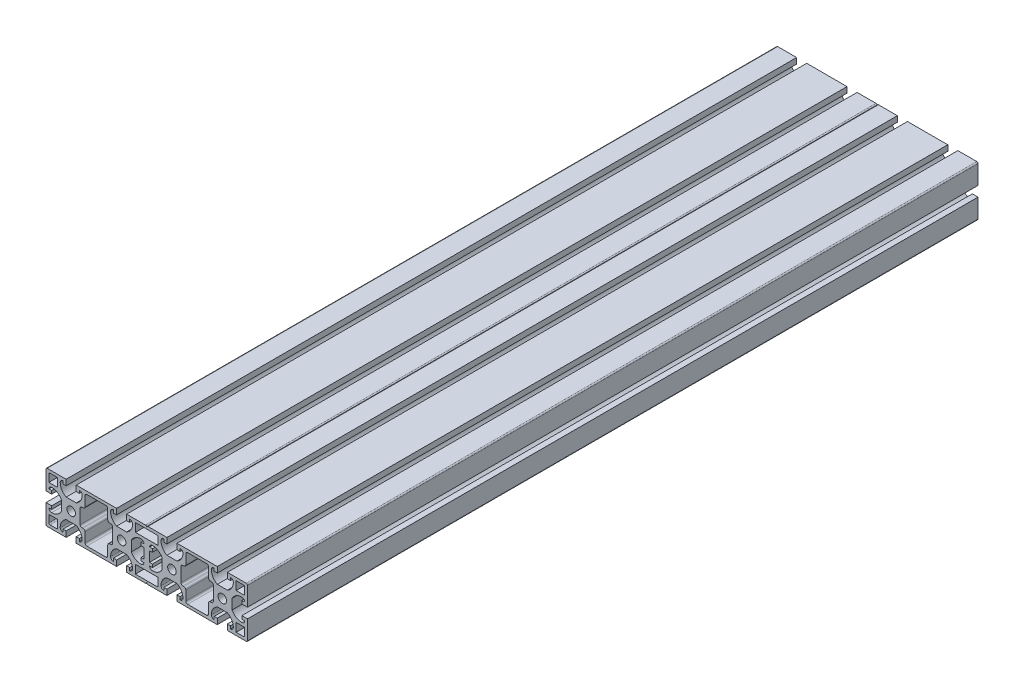
SolidWorks part; units mm, degrees
material "3.0255 (EN-AW 1350A)"
ref_plane "Płaszczyzna przednia" through (0, 0, 0) normal (0, 0, 1) x (1, 0, 0)
ref_plane "Płaszczyzna górna" through (0, 0, 0) normal (0, 1, 0) x (1, 0, 0)
ref_plane "Płaszczyzna prawa" through (0, 0, 0) normal (1, 0, 0) x (0, 0, -1)
sketch "Szkic1" plane through (0, 0, 0) normal (0, 0, 1) x (1, 0, 0)
  line L0 (0, 20) -> (0, -20) construction
  line L1 (-51.8865, 0) -> (40, 0) construction
  line L4 (-40, -19) -> (-40, 19)
  line L7 (-40, -20) -> (0, 0) construction
  line L8 (-40, 20) -> (40, -20) construction
  line L13 (20, 20) -> (20, 0) construction
  line L15 (24, 20) -> (24, 15.5)
  line L16 (24, 15.5) -> (26.4714, 15.5)
  line L21 (16, 15.5) -> (13.5286, 15.5)
  line L23 (16, 20) -> (13.5286, 20)
  line L24 (16, 20) -> (16, 15.5)
  line L25 (16, 7.75) -> (24, 7.75)
  line L26 (13.5286, 15.5) -> (13.5286, 17.75)
  line L27 (26.4714, 15.5) -> (26.4714, 17.75)
  line L28 (-24, 20) -> (-24, 15.5)
  line L29 (-26.4714, 15.5) -> (-26.4714, 17.75)
  line L30 (-24, 15.5) -> (-26.4714, 15.5)
  line L31 (-13.5286, 15.5) -> (-13.5286, 17.75)
  line L32 (-16, 15.5) -> (-13.5286, 15.5)
  line L33 (-16, 20) -> (-16, 15.5)
  line L34 (-16, 7.75) -> (-24, 7.75)
  line L35 (20, -20) -> (20, 0) construction
  line L36 (-40, -20) -> (0, 0) construction
  line L37 (-40, 20) -> (40, -20) construction
  line L38 (30.9714, -17.75) -> (36.75, -17.75)
  line L39 (-16, -7.75) -> (-24, -7.75)
  line L40 (-16, -20) -> (-16, -15.5)
  line L41 (-16, -15.5) -> (-13.5286, -15.5)
  line L42 (-13.5286, -15.5) -> (-13.5286, -17.75)
  line L43 (-24, -15.5) -> (-26.4714, -15.5)
  line L44 (-26.4714, -15.5) -> (-26.4714, -17.75)
  line L45 (-24, -20) -> (-24, -15.5)
  line L46 (26.4714, -15.5) -> (26.4714, -17.75)
  line L47 (13.5286, -15.5) -> (13.5286, -17.75)
  line L48 (16, -7.75) -> (24, -7.75)
  line L49 (16, -20) -> (16, -15.5)
  line L50 (16, -15.5) -> (13.5286, -15.5)
  line L51 (24, -15.5) -> (26.4714, -15.5)
  line L52 (24, -20) -> (24, -15.5)
  line L53 (40, -20) -> (0, 20) construction
  line L54 (35.5, 6.4714) -> (37.75, 6.4714)
  line L55 (35.5, 4) -> (35.5, 6.4714)
  line L56 (40, 4) -> (35.5, 4)
  line L57 (40, -4) -> (35.5, -4)
  line L58 (35.5, -4) -> (35.5, -6.4714)
  line L59 (35.5, -6.4714) -> (37.75, -6.4714)
  line L60 (27.75, 4) -> (27.75, -4)
  line L61 (-35.5, -6.4714) -> (-37.75, -6.4714)
  line L62 (-37.75, -4) -> (-35.5, -4)
  line L63 (-35.5, -4) -> (-35.5, -6.4714)
  line L64 (-35.5, 4) -> (-35.5, 6.4714)
  line L65 (-35.5, 6.4714) -> (-37.75, 6.4714)
  line L66 (-37.75, 4) -> (-35.5, 4)
  line L67 (-27.75, 4) -> (-27.75, -4)
  line L68 (-37.75, 4) -> (-37.75, -4)
  line L69 (40, -4) -> (40, -19)
  line L70 (40, 19) -> (40, 4)
  line L71 (-39, -20) -> (-24, -20)
  line L72 (-16, -20) -> (16, -20)
  line L73 (24, -20) -> (39, -20)
  line L74 (13.5286, 20) -> (-16, 20)
  line L75 (-24, 20) -> (-39, 20)
  line L76 (24, 20) -> (39, 20)
  line L77 (10.5286, 7.0902) -> (11.4095, 7.0902)
  line L78 (-7.5286, -17.75) -> (7.5286, -17.75)
  line L79 (-9.0286, -16.25) -> (-9.0286, -8.5902)
  line L80 (-7.5286, 17.75) -> (7.5286, 17.75)
  line L81 (9.0286, -16.25) -> (9.0286, -8.5902)
  line L82 (-9.0286, -17.75) -> (9.0286, 17.75) construction
  line L83 (-9.0286, 17.75) -> (9.0286, -17.75) construction
  line L84 (-11.4095, -7.0902) -> (-10.5286, -7.0902)
  line L85 (-12.9095, -5.5902) -> (-12.9095, 5.5902)
  line L86 (-11.4095, 7.0902) -> (-10.5286, 7.0902)
  line L87 (12.9095, -5.5902) -> (12.9095, 5.5902)
  line L88 (-12.9095, -7.0902) -> (0, 0) construction
  line L89 (-12.9095, 7.0902) -> (12.9095, -7.0902) construction
  line L90 (-9.0286, 8.5902) -> (-9.0286, 16.25)
  line L91 (-9.0286, 4.5143) -> (-9.0286, 4.9587)
  line L92 (-9.0286, -4.9587) -> (-9.0286, -4.5143)
  line L93 (9.0286, 8.5902) -> (9.0286, 16.25)
  line L94 (10.5286, -7.0902) -> (11.4095, -7.0902)
  line L96 (0, 0) -> (12.9095, 7.0902) construction
  line L98 (37.75, -10.9714) -> (37.75, -16.75)
  line L99 (30.9714, 10.9714) -> (37.75, 10.9714)
  line L100 (30.9714, 10.9714) -> (30.9714, 17.75)
  line L101 (30.9714, 17.75) -> (36.75, 17.75)
  line L102 (37.75, 10.9714) -> (37.75, 16.75)
  line L103 (30.9714, 10.9714) -> (37.75, 17.75) construction
  line L104 (30.9714, 17.75) -> (37.75, 10.9714) construction
  line L105 (30.9714, -10.9714) -> (37.75, -10.9714)
  line L106 (30.9714, -10.9714) -> (30.9714, -17.75)
  line L107 (-30.9714, -10.9714) -> (-30.9714, -17.75)
  line L108 (-30.9714, -10.9714) -> (-37.75, -10.9714)
  line L109 (-37.75, -10.9714) -> (-37.75, -16.75)
  line L110 (-30.9714, -17.75) -> (-36.75, -17.75)
  line L111 (-30.9714, 17.75) -> (-36.75, 17.75)
  line L112 (-37.75, 10.9714) -> (-37.75, 16.75)
  line L113 (-30.9714, 10.9714) -> (-37.75, 10.9714)
  line L114 (-30.9714, 10.9714) -> (-30.9714, 17.75)
  line L115 (-40, 52.1634) -> (-40, -64.8993) construction
  line L116 (-110.9714, 17.75) -> (-117.75, 10.9714) construction
  line L117 (-110.9714, 10.9714) -> (-117.75, 17.75) construction
  line L118 (-80, 0) -> (-92.9095, 7.0902) construction
  line L119 (-67.0905, 7.0902) -> (-92.9095, -7.0902) construction
  line L120 (-67.0905, -7.0902) -> (-80, 0) construction
  line L121 (-70.9714, 17.75) -> (-89.0286, -17.75) construction
  line L122 (-70.9714, -17.75) -> (-89.0286, 17.75) construction
  line L123 (-120, -20) -> (-80, 20) construction
  line L124 (-40, 20) -> (-120, -20) construction
  line L125 (-40, -20) -> (-80, 0) construction
  line L126 (-100, -20) -> (-100, 0) construction
  line L127 (-100, 20) -> (-100, 0) construction
  line L128 (-40, 20) -> (-120, -20) construction
  line L129 (-40, -20) -> (-80, 0) construction
  line L130 (-28.1135, 0) -> (-120, 0) construction
  line L131 (-80, 20) -> (-80, -20) construction
  line L132 (-49.0286, 10.9714) -> (-49.0286, 17.75)
  line L133 (-49.0286, 10.9714) -> (-42.25, 10.9714)
  line L134 (-42.25, 10.9714) -> (-42.25, 16.75)
  line L135 (-49.0286, 17.75) -> (-43.25, 17.75)
  line L136 (-49.0286, -17.75) -> (-43.25, -17.75)
  line L137 (-42.25, -10.9714) -> (-42.25, -16.75)
  line L138 (-49.0286, -10.9714) -> (-42.25, -10.9714)
  line L139 (-49.0286, -10.9714) -> (-49.0286, -17.75)
  line L140 (-110.9714, -10.9714) -> (-110.9714, -17.75)
  line L141 (-110.9714, -10.9714) -> (-117.75, -10.9714)
  line L142 (-117.75, 10.9714) -> (-117.75, 16.75)
  line L143 (-110.9714, 17.75) -> (-116.75, 17.75)
  line L144 (-110.9714, 10.9714) -> (-110.9714, 17.75)
  line L145 (-110.9714, 10.9714) -> (-117.75, 10.9714)
  line L146 (-117.75, -10.9714) -> (-117.75, -16.75)
  line L147 (-90.5286, -7.0902) -> (-91.4095, -7.0902)
  line L148 (-89.0286, 8.5902) -> (-89.0286, 16.25)
  line L149 (-70.9714, -4.9587) -> (-70.9714, -4.5143)
  line L150 (-70.9714, 4.5143) -> (-70.9714, 4.9587)
  line L151 (-70.9714, 8.5902) -> (-70.9714, 16.25)
  line L152 (-92.9095, -5.5902) -> (-92.9095, 5.5902)
  line L153 (-68.5905, 7.0902) -> (-69.4714, 7.0902)
  line L154 (-67.0905, -5.5902) -> (-67.0905, 5.5902)
  line L155 (-68.5905, -7.0902) -> (-69.4714, -7.0902)
  line L156 (-89.0286, -16.25) -> (-89.0286, -8.5902)
  line L157 (-72.4714, 17.75) -> (-87.5286, 17.75)
  line L158 (-70.9714, -16.25) -> (-70.9714, -8.5902)
  line L159 (-72.4714, -17.75) -> (-87.5286, -17.75)
  line L160 (-90.5286, 7.0902) -> (-91.4095, 7.0902)
  line L161 (-104, 20) -> (-119, 20)
  line L162 (-56, 20) -> (-41, 20)
  line L163 (-93.5286, 20) -> (-64, 20)
  line L164 (-104, -20) -> (-119, -20)
  line L165 (-64, -20) -> (-96, -20)
  line L166 (-41, -20) -> (-56, -20)
  line L167 (-120, 19) -> (-120, 4)
  line L168 (-120, -4) -> (-120, -19)
  line L169 (-42.25, 4) -> (-42.25, -4)
  line L170 (-52.25, 4) -> (-52.25, -4)
  line L171 (-42.25, 4) -> (-44.5, 4)
  line L172 (-44.5, 6.4714) -> (-42.25, 6.4714)
  line L173 (-44.5, 4) -> (-44.5, 6.4714)
  line L174 (-44.5, -4) -> (-44.5, -6.4714)
  line L175 (-42.25, -4) -> (-44.5, -4)
  line L176 (-44.5, -6.4714) -> (-42.25, -6.4714)
  line L177 (-107.75, 4) -> (-107.75, -4)
  line L178 (-115.5, -6.4714) -> (-117.75, -6.4714)
  line L179 (-115.5, -4) -> (-115.5, -6.4714)
  line L180 (-120, -4) -> (-115.5, -4)
  line L181 (-120, 4) -> (-115.5, 4)
  line L182 (-115.5, 4) -> (-115.5, 6.4714)
  line L183 (-115.5, 6.4714) -> (-117.75, 6.4714)
  line L184 (-104, -20) -> (-104, -15.5)
  line L185 (-104, -15.5) -> (-106.4714, -15.5)
  line L186 (-96, -15.5) -> (-93.5286, -15.5)
  line L187 (-96, -20) -> (-96, -15.5)
  line L188 (-96, -7.75) -> (-104, -7.75)
  line L189 (-93.5286, -15.5) -> (-93.5286, -17.75)
  line L190 (-106.4714, -15.5) -> (-106.4714, -17.75)
  line L191 (-56, -20) -> (-56, -15.5)
  line L192 (-53.5286, -15.5) -> (-53.5286, -17.75)
  line L193 (-56, -15.5) -> (-53.5286, -15.5)
  line L194 (-66.4714, -15.5) -> (-66.4714, -17.75)
  line L195 (-64, -15.5) -> (-66.4714, -15.5)
  line L196 (-64, -20) -> (-64, -15.5)
  line L197 (-64, -7.75) -> (-56, -7.75)
  line L198 (-110.9714, -17.75) -> (-116.75, -17.75)
  line L199 (-64, 7.75) -> (-56, 7.75)
  line L200 (-64, 20) -> (-64, 15.5)
  line L201 (-64, 15.5) -> (-66.4714, 15.5)
  line L202 (-66.4714, 15.5) -> (-66.4714, 17.75)
  line L203 (-56, 15.5) -> (-53.5286, 15.5)
  line L204 (-53.5286, 15.5) -> (-53.5286, 17.75)
  line L205 (-56, 20) -> (-56, 15.5)
  line L206 (-106.4714, 15.5) -> (-106.4714, 17.75)
  line L207 (-93.5286, 15.5) -> (-93.5286, 17.75)
  line L208 (-96, 7.75) -> (-104, 7.75)
  line L209 (-96, 20) -> (-96, 15.5)
  line L210 (-96, 20) -> (-93.5286, 20)
  line L211 (-96, 15.5) -> (-93.5286, 15.5)
  line L212 (-104, 15.5) -> (-106.4714, 15.5)
  line L213 (-104, 20) -> (-104, 15.5)
  line L214 (-41, 20) -> (-39, 20)
  line L215 (-43.25, 17.75) -> (-36.75, 17.75)
  line L216 (-42.25, 10.9714) -> (-37.75, 10.9714)
  line L217 (-42.25, -10.9714) -> (-37.75, -10.9714)
  line L218 (-43.25, -17.75) -> (-36.75, -17.75)
  line L219 (-41, -20) -> (-39, -20)
  circle A0 centre (-20, 0) radius 3.4
  circle A1 centre (20, 0) radius 3.4
  arc A2 (26.4714, 17.75) -> (28.7214, 15.5) centre (26.4714, 15.5) cw
  arc A3 (28.7214, 15.5) -> (24, 7.75) centre (20, 15.5) cw
  arc A4 (13.5286, 17.75) -> (11.2786, 15.5) centre (13.5286, 15.5) ccw
  arc A5 (11.2786, 15.5) -> (16, 7.75) centre (20, 15.5) ccw
  arc A6 (-26.4714, 17.75) -> (-28.7214, 15.5) centre (-26.4714, 15.5) ccw
  arc A7 (-13.5286, 17.75) -> (-11.2786, 15.5) centre (-13.5286, 15.5) cw
  arc A8 (-11.2786, 15.5) -> (-16, 7.75) centre (-20, 15.5) cw
  arc A9 (-28.7214, 15.5) -> (-24, 7.75) centre (-20, 15.5) ccw
  arc A10 (-28.7214, -15.5) -> (-24, -7.75) centre (-20, -15.5) cw
  arc A11 (-11.2786, -15.5) -> (-16, -7.75) centre (-20, -15.5) ccw
  arc A12 (-13.5286, -17.75) -> (-11.2786, -15.5) centre (-13.5286, -15.5) ccw
  arc A13 (-26.4714, -17.75) -> (-28.7214, -15.5) centre (-26.4714, -15.5) cw
  arc A14 (11.2786, -15.5) -> (16, -7.75) centre (20, -15.5) cw
  arc A15 (13.5286, -17.75) -> (11.2786, -15.5) centre (13.5286, -15.5) cw
  arc A16 (28.7214, -15.5) -> (24, -7.75) centre (20, -15.5) ccw
  arc A17 (26.4714, -17.75) -> (28.7214, -15.5) centre (26.4714, -15.5) ccw
  arc A18 (35.5, 8.7214) -> (27.75, 4) centre (35.5, 0) ccw
  arc A19 (37.75, 6.4714) -> (35.5, 8.7214) centre (35.5, 6.4714) ccw
  arc A20 (37.75, -6.4714) -> (35.5, -8.7214) centre (35.5, -6.4714) cw
  arc A21 (35.5, -8.7214) -> (27.75, -4) centre (35.5, 0) cw
  arc A22 (-35.5, -8.7214) -> (-27.75, -4) centre (-35.5, 0) ccw
  arc A23 (-37.75, -6.4714) -> (-35.5, -8.7214) centre (-35.5, -6.4714) ccw
  arc A24 (-37.75, 6.4714) -> (-35.5, 8.7214) centre (-35.5, 6.4714) cw
  arc A25 (-35.5, 8.7214) -> (-27.75, 4) centre (-35.5, 0) cw
  arc A26 (-10.5286, 7.0902) -> (-9.0286, 8.5902) centre (-10.5286, 8.5902) ccw
  arc A27 (-9.0286, -8.5902) -> (-10.5286, -7.0902) centre (-10.5286, -8.5902) ccw
  arc A28 (11.4095, -7.0902) -> (12.9095, -5.5902) centre (11.4095, -5.5902) ccw
  arc A29 (9.0286, -8.5902) -> (10.5286, -7.0902) centre (10.5286, -8.5902) cw
  arc A30 (7.5286, -17.75) -> (9.0286, -16.25) centre (7.5286, -16.25) ccw
  arc A31 (-7.5286, -17.75) -> (-9.0286, -16.25) centre (-7.5286, -16.25) cw
  arc A32 (-11.4095, -7.0902) -> (-12.9095, -5.5902) centre (-11.4095, -5.5902) cw
  arc A33 (-12.9095, 5.5902) -> (-11.4095, 7.0902) centre (-11.4095, 5.5902) cw
  arc A34 (-9.0286, 16.25) -> (-7.5286, 17.75) centre (-7.5286, 16.25) cw
  arc A35 (7.5286, 17.75) -> (9.0286, 16.25) centre (7.5286, 16.25) cw
  arc A36 (11.4095, 7.0902) -> (12.9095, 5.5902) centre (11.4095, 5.5902) cw
  arc A37 (10.5286, 7.0902) -> (9.0286, 8.5902) centre (10.5286, 8.5902) cw
  arc A38 (-40, 19) -> (-39, 20) centre (-39, 19) cw
  arc A39 (-39, -20) -> (-40, -19) centre (-39, -19) cw
  arc A40 (39, -20) -> (40, -19) centre (39, -19) ccw
  arc A41 (39, 20) -> (40, 19) centre (39, 19) cw
  arc A42 (36.75, 17.75) -> (37.75, 16.75) centre (36.75, 16.75) cw
  arc A43 (36.75, -17.75) -> (37.75, -16.75) centre (36.75, -16.75) ccw
  arc A44 (-36.75, -17.75) -> (-37.75, -16.75) centre (-36.75, -16.75) cw
  arc A45 (-36.75, 17.75) -> (-37.75, 16.75) centre (-36.75, 16.75) ccw
  arc A46 (-43.25, 17.75) -> (-42.25, 16.75) centre (-43.25, 16.75) cw
  arc A47 (-43.25, -17.75) -> (-42.25, -16.75) centre (-43.25, -16.75) ccw
  arc A48 (-116.75, -17.75) -> (-117.75, -16.75) centre (-116.75, -16.75) cw
  arc A49 (-116.75, 17.75) -> (-117.75, 16.75) centre (-116.75, 16.75) ccw
  arc A50 (-119, 20) -> (-120, 19) centre (-119, 19) ccw
  arc A51 (-119, -20) -> (-120, -19) centre (-119, -19) cw
  arc A52 (-41, -20) -> (-40, -19) centre (-41, -19) ccw
  arc A53 (-40, 19) -> (-41, 20) centre (-41, 19) ccw
  arc A54 (-90.5286, 7.0902) -> (-89.0286, 8.5902) centre (-90.5286, 8.5902) ccw
  arc A55 (-91.4095, 7.0902) -> (-92.9095, 5.5902) centre (-91.4095, 5.5902) ccw
  arc A56 (-87.5286, 17.75) -> (-89.0286, 16.25) centre (-87.5286, 16.25) ccw
  arc A57 (-70.9714, 16.25) -> (-72.4714, 17.75) centre (-72.4714, 16.25) ccw
  arc A58 (-67.0905, 5.5902) -> (-68.5905, 7.0902) centre (-68.5905, 5.5902) ccw
  arc A59 (-68.5905, -7.0902) -> (-67.0905, -5.5902) centre (-68.5905, -5.5902) ccw
  arc A60 (-72.4714, -17.75) -> (-70.9714, -16.25) centre (-72.4714, -16.25) ccw
  arc A61 (-87.5286, -17.75) -> (-89.0286, -16.25) centre (-87.5286, -16.25) cw
  arc A62 (-89.0286, -8.5902) -> (-90.5286, -7.0902) centre (-90.5286, -8.5902) ccw
  arc A63 (-91.4095, -7.0902) -> (-92.9095, -5.5902) centre (-91.4095, -5.5902) cw
  arc A64 (-70.9714, -8.5902) -> (-69.4714, -7.0902) centre (-69.4714, -8.5902) cw
  arc A65 (-69.4714, 7.0902) -> (-70.9714, 8.5902) centre (-69.4714, 8.5902) cw
  arc A66 (-44.5, 8.7214) -> (-52.25, 4) centre (-44.5, 0) ccw
  arc A67 (-42.25, 6.4714) -> (-44.5, 8.7214) centre (-44.5, 6.4714) ccw
  arc A68 (-42.25, -6.4714) -> (-44.5, -8.7214) centre (-44.5, -6.4714) cw
  arc A69 (-44.5, -8.7214) -> (-52.25, -4) centre (-44.5, 0) cw
  arc A70 (-115.5, -8.7214) -> (-107.75, -4) centre (-115.5, 0) ccw
  arc A71 (-117.75, -6.4714) -> (-115.5, -8.7214) centre (-115.5, -6.4714) ccw
  arc A72 (-117.75, 6.4714) -> (-115.5, 8.7214) centre (-115.5, 6.4714) cw
  arc A73 (-115.5, 8.7214) -> (-107.75, 4) centre (-115.5, 0) cw
  arc A74 (-106.4714, -17.75) -> (-108.7214, -15.5) centre (-106.4714, -15.5) cw
  arc A75 (-108.7214, -15.5) -> (-104, -7.75) centre (-100, -15.5) cw
  arc A76 (-93.5286, -17.75) -> (-91.2786, -15.5) centre (-93.5286, -15.5) ccw
  arc A77 (-91.2786, -15.5) -> (-96, -7.75) centre (-100, -15.5) ccw
  arc A78 (-53.5286, -17.75) -> (-51.2786, -15.5) centre (-53.5286, -15.5) ccw
  arc A79 (-66.4714, -17.75) -> (-68.7214, -15.5) centre (-66.4714, -15.5) cw
  arc A80 (-68.7214, -15.5) -> (-64, -7.75) centre (-60, -15.5) cw
  arc A81 (-51.2786, -15.5) -> (-56, -7.75) centre (-60, -15.5) ccw
  arc A82 (-51.2786, 15.5) -> (-56, 7.75) centre (-60, 15.5) cw
  arc A83 (-68.7214, 15.5) -> (-64, 7.75) centre (-60, 15.5) ccw
  arc A84 (-66.4714, 17.75) -> (-68.7214, 15.5) centre (-66.4714, 15.5) ccw
  arc A85 (-53.5286, 17.75) -> (-51.2786, 15.5) centre (-53.5286, 15.5) cw
  arc A86 (-91.2786, 15.5) -> (-96, 7.75) centre (-100, 15.5) cw
  arc A87 (-93.5286, 17.75) -> (-91.2786, 15.5) centre (-93.5286, 15.5) cw
  arc A88 (-108.7214, 15.5) -> (-104, 7.75) centre (-100, 15.5) ccw
  arc A89 (-106.4714, 17.75) -> (-108.7214, 15.5) centre (-106.4714, 15.5) ccw
  circle A90 centre (-100, 0) radius 3.4
  circle A91 centre (-60, 0) radius 3.4
  point P5 (0, 0)
  point P17 (0, 0)
  point P30 (24, 17.75)
  point P108 (0, 0)
  point P124 (-9.0286, 7.0902)
  point P132 (9.0286, -7.0902)
  point P156 (9.0286, 7.0902)
  point P161 (40, 20)
  point P162 (34.3607, 14.3607)
  point P364 (-114.3607, 14.3607)
  point P365 (-120, 20)
  point P366 (-89.0286, 7.0902)
  point P367 (-89.0286, -7.0902)
  point P368 (-70.9714, 7.0902)
  point P369 (-80, 0)
  point P370 (-80, 0)
  point P371 (-80, 0)
  dimension "D4" = 6.8
  dimension "D5" = 12.25
  dimension "D9" = 11
  dimension "D11" = 1.5
  dimension "D12" = 1
  dimension "D16" = 1
  dimension "D1" = 80
  dimension "D2" = 40
  dimension "D3" = 40
  dimension "D6" = 2.25
  dimension "D7" = 8
  dimension "D8" = 4.5
  dimension "D10" = 14.1804
  dimension "D13" = 2.25
  dimension "D14" = 2.25
  dimension "D15" = 2.25
extrude "Dodanie-wyciągnięcie1" add sketch "Szkic1" along normal blind 580 contours A20 A21 L60 A18 A19 L54 L55 L56 L70 L76 L15 L16 L27 A2 A3 L25 A5 A4 L26 L21 L24 L23 L74 L33 L32 L31 A7 A8 L34 A9 A6 L29 L30 L28 L75 L4 L71 L45 L43 L44 A13 A10 L39 A11 A12 L42 L41 L40 L72 L49 L50 | A89 L206 L212 L213 L161 A50 L167 L181 L182 L183 A72 A73 L177 A70 A71 L178 L179 L180 L168 A51 L164 L184 L185 L190 A74 A75 L188 A77 A76 L189 L186 L187 L165 L196 L195 L194 A79 A80 L197 A81 A78 L192 L193 L191 L166 A52 L4 L218 L136 L139 L138
